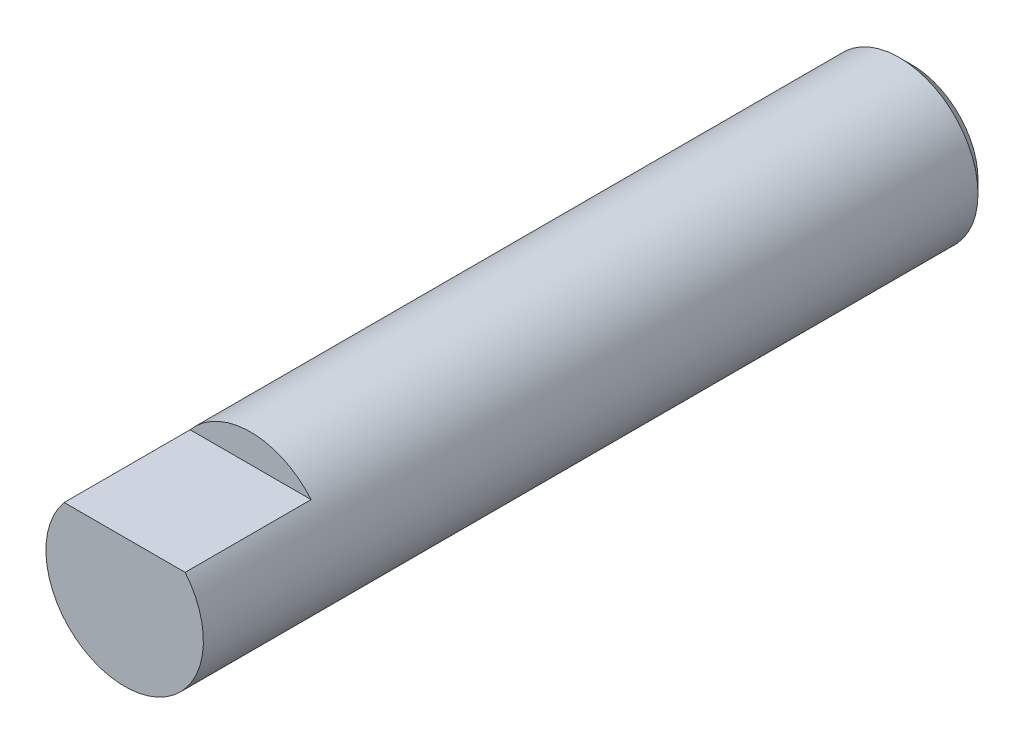
SolidWorks part; units mm, degrees
material "ABS"
ref_plane "Front Plane" through (0, 0, 0) normal (0, 0, 1) x (1, 0, 0)
ref_plane "Top Plane" through (0, 0, 0) normal (0, 1, 0) x (1, 0, 0)
ref_plane "Right Plane" through (0, 0, 0) normal (1, 0, 0) x (0, 0, -1)
sketch "Sketch1" plane through (0, 0, 0) normal (0, 0, 1) x (1, 0, 0)
  circle A0 centre (0, 0) radius 12.5
  dimension "D1" = 25
extrude "Boss-Extrude1" add sketch "Sketch1" along normal blind 125
sketch "Sketch2" plane through (0, 0, 125) normal (0, 0, 1) x (1, 0, 0)
  line L0 (-9.6047, 8) -> (9.6047, 8)
  arc A0 (9.6047, 8) -> (-9.6047, 8) centre (0, 0) ccw
  dimension "D1" = 25
  dimension "D2" = 8
extrude "Cut-Extrude1" cut sketch "Sketch2" against normal blind 20
chamfer "Chamfer1" distance 2 angle 45 1 edges at (12.5, 0, 0)
